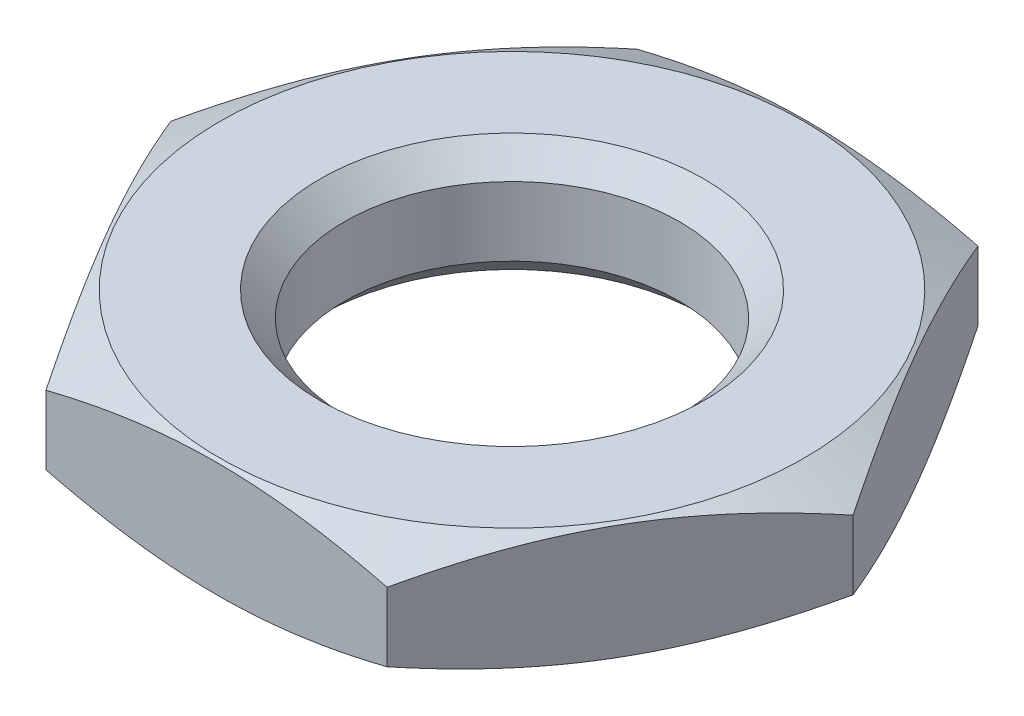
SolidWorks part; units mm, degrees
material "Brass"
ref_plane "Front Plane" through (0, 0, 0) normal (0, 0, 1) x (1, 0, 0)
ref_plane "Top Plane" through (0, 0, 0) normal (0, 1, 0) x (1, 0, 0)
ref_plane "Right Plane" through (0, 0, 0) normal (1, 0, 0) x (0, 0, -1)
sketch "Sketch1" plane through (0, 0, 0) normal (0, 1, 0) x (1, 0, 0)
  line L1 (3.4641, 6) -> (-3.4641, 6)
  line L2 (-3.4641, 6) -> (-6.9282, 0)
  line L3 (-6.9282, 0) -> (-3.4641, -6)
  line L4 (-3.4641, -6) -> (3.4641, -6)
  line L5 (3.4641, -6) -> (6.9282, 0)
  line L6 (6.9282, 0) -> (3.4641, 6)
  circle A0 centre (0, 0) radius 6 construction
  circle A1 centre (0, 0) radius 3.4
  dimension "D2" = 6.8
  dimension "D1" = 12
extrude "Boss-Extrude1" add sketch "Sketch1" along normal mid plane 2.4
chamfer "Chamfer1" distance 0.5 angle 45 2 edges at (0, -1.2, 3.4) (0, 1.2, 3.4)
sketch "Sketch3" plane through (0, 0, 0) normal (0, 0, 1) x (1, 0, 0)
  line L0 (6.9282, 1.2) -> (6.9282, 0.7)
  line L1 (6.9282, 1.2) -> (6.9282, -1.2) construction
  line L2 (6.9282, 0.7) -> (5.9282, 1.2)
  line L3 (6.9282, 1.2) -> (3.4641, 1.2) construction
  line L4 (5.9282, 1.2) -> (6.9282, 1.2)
  line L5 (0, 0) -> (0, 50000) construction
  line L6 (0, 0) -> (-50000, 0) construction
  line L7 (5.9282, -1.2) -> (6.9282, -1.2)
  line L8 (6.9282, -0.7) -> (5.9282, -1.2)
  line L9 (6.9282, -1.2) -> (6.9282, -0.7)
  dimension "D1" = 1
  dimension "D2" = 0.5
revolve "Cut-Revolve1" cut sketch "Sketch3" angle 360 about L5
